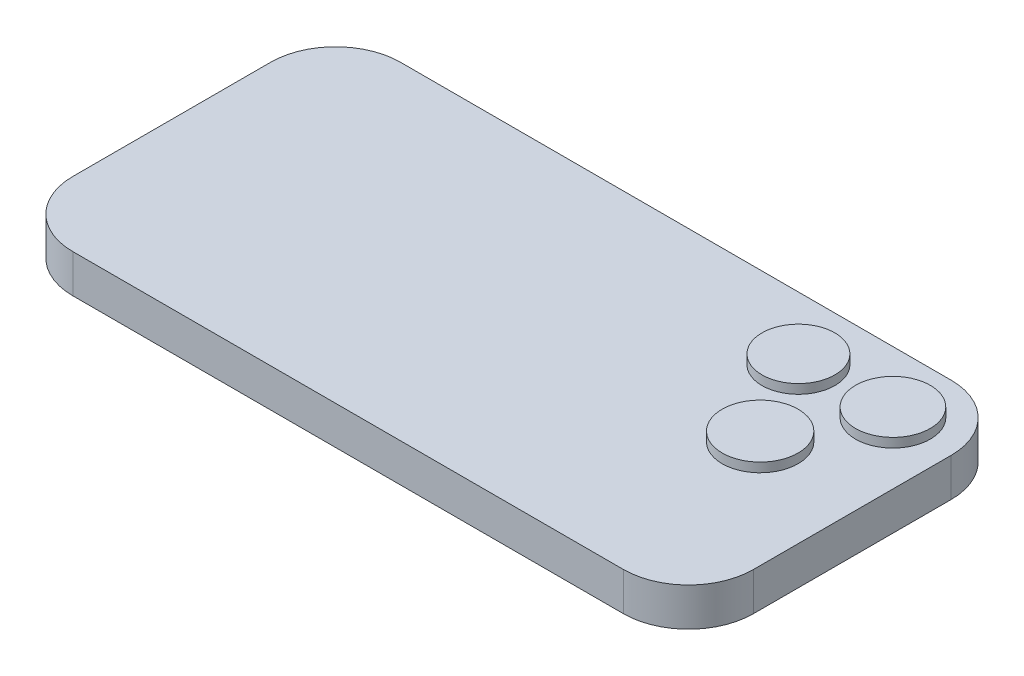
SolidWorks part; units mm, degrees
ref_plane "Front Plane" through (0, 0, 0) normal (0, 0, 1) x (1, 0, 0)
ref_plane "Top Plane" through (0, 0, 0) normal (0, 1, 0) x (1, 0, 0)
ref_plane "Right Plane" through (0, 0, 0) normal (1, 0, 0) x (0, 0, -1)
sketch "Sketch1" plane through (0, 0, 0) normal (0, 1, 0) x (1, 0, 0)
  line L1 (73.3, -35.3) -> (-73.3, -35.3)
  line L2 (73.3, -35.3) -> (73.3, 35.3)
  line L3 (73.3, 35.3) -> (-73.3, 35.3)
  line L4 (-73.3, -35.3) -> (-73.3, 35.3)
  line L5 (73.3, -35.3) -> (-73.3, 35.3) construction
  line L6 (73.3, 35.3) -> (-73.3, -35.3) construction
  point P0 (0, 0)
  dimension "D1" = 70.6
  dimension "D2" = 146.6
extrude "Boss-Extrude1" add sketch "Sketch1" along normal blind 8.25
fillet "Fillet1" radius 14 4 edges at (73.3, 4.125, -35.3) (73.3, 4.125, 35.3) (-73.3, 4.125, -35.3) (-73.3, 4.125, 35.3)
sketch "Sketch2" plane through (0, 8.25, 0) normal (0, 1, 0) x (1, 0, 0)
  line L1 (70.9195, -8.5159) -> (28.704, -8.5159) construction
  line L2 (70.9195, -8.5159) -> (70.9195, 32.7273) construction
  line L3 (70.9195, 32.7273) -> (28.704, 32.7273) construction
  line L4 (28.704, -8.5159) -> (28.704, 32.7273) construction
  line L5 (70.9195, -8.5159) -> (28.704, 32.7273) construction
  line L6 (70.9195, 32.7273) -> (28.704, -8.5159) construction
  circle A0 centre (39.9298, 21.76) radius 7.8441
  circle A1 centre (59.9909, 22.0503) radius 8.0498
  circle A3 centre (50.2108, 3.2373) radius 8.1781
  point P0 (49.8118, 12.1057)
  point P9 (50.2108, 3.2373)
  point P10 (60.0669, 21.9725)
  point P15 (60.3307, 5.998)
  point P16 (55.8796, 3.4441)
  point P17 (39.9298, 21.76)
  point P18 (36.871, 4.8942)
extrude "Boss-Extrude2" add sketch "Sketch2" along normal blind 2
